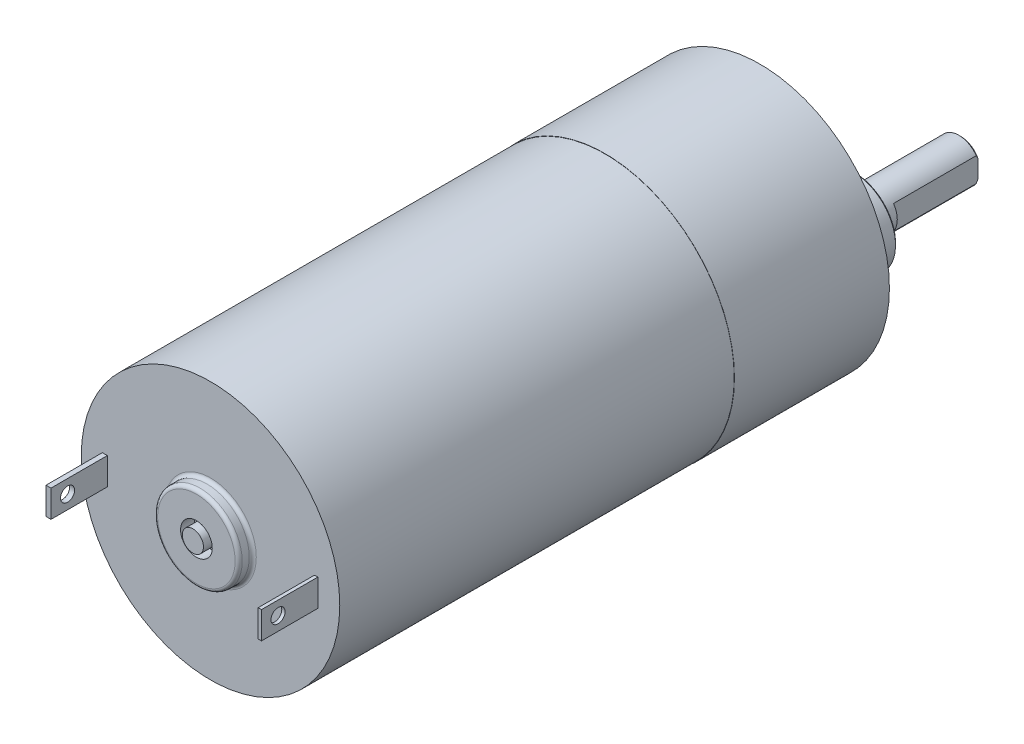
SolidWorks part; units mm, degrees
ref_plane "Plan de face" through (0, 0, 0) normal (0, 0, 1) x (1, 0, 0)
ref_plane "Plan de dessus" through (0, 0, 0) normal (0, 1, 0) x (1, 0, 0)
ref_plane "Plan de droite" through (0, 0, 0) normal (1, 0, 0) x (0, 0, -1)
sketch "Esquisse1" plane through (0, 0, 0) normal (0, 0, 1) x (1, 0, 0)
  circle A0 centre (0, 0) radius 18.385
  dimension "D1" = 36.77
extrude "Boss.-Extru.1" add sketch "Esquisse1" along normal blind 22
sketch "Esquisse2" plane through (0, 0, 22) normal (0, 0, 1) x (1, 0, 0)
  circle A0 centre (0, 0) radius 18.35
  dimension "D1" = 36.7
extrude "Boss.-Extru.2" add sketch "Esquisse2" along normal blind 56
sketch "Esquisse3" plane through (0, 0, 78) normal (0, 0, 1) x (1, 0, 0)
  circle A0 centre (0, 0) radius 6
  dimension "D1" = 12
extrude "Boss.-Extru.3" add sketch "Esquisse3" along normal blind 2
fillet "Congé1" radius 0.5 2 edges at (6, 0, 78) (6, 0, 80)
sketch "Esquisse4" plane through (0, 0, 80) normal (0, 0, 1) x (1, 0, 0)
  circle A0 centre (0, 0) radius 2.25
  dimension "D1" = 4.5
extrude "Enlèv. mat.-Extru.1" cut sketch "Esquisse4" against normal blind 2
sketch "Esquisse5" plane through (0, 0, 78) normal (0, 0, 1) x (1, 0, 0)
  circle A0 centre (0, 0) radius 1.5
  dimension "D1" = 3
extrude "Boss.-Extru.4" add sketch "Esquisse5" along normal blind 2.5
ref_plane "Plan1" through (0, 0, 74.5) normal (0, 0, 1) x (1, 0, 0)
sketch "Esquisse7" plane through (0, 0, 74.5) normal (0, 0, 1) x (1, 0, 0)
  circle A0 centre (0, 0) radius 15.25
  circle A1 centre (0, 0) radius 15.5
  dimension "D1" = 30.5
  dimension "D2" = 31
extrude "Boss.-Extru.5" add sketch "Esquisse7" against normal blind 50 separate body
sketch "Esquisse8" plane through (0, 0, 0) normal (0, 0, -1) x (-1, 0, 0)
  line L0 (-18.385, 0) -> (-18.5, 13.0609) construction
  line L1 (-13.5, 0) -> (-13.5, 12.4803) construction
  circle A0 centre (-7.5, 0) radius 6
  circle A1 centre (0, 0) radius 18.385 construction
  dimension "D1" = 12
  dimension "D2" = 7.5
extrude "Boss.-Extru.6" add sketch "Esquisse8" along normal blind 6 separate body
sketch "Esquisse9" plane through (0, 0, -6) normal (0, 0, -1) x (-1, 0, 0)
  circle A0 centre (-7.5, 0) radius 3
extrude "Boss.-Extru.7" add sketch "Esquisse9" along normal blind 15
sketch "Esquisse10" plane through (0, 0, -21) normal (0, 0, -1) x (-1, 0, 0)
  line L0 (-9.96, 1.7171) -> (-9.96, -1.7171)
  line L1 (-9.96, -1.7171) -> (-14.4902, -1.7171)
  line L2 (-14.4902, -1.7171) -> (-14.4902, 1.7171)
  line L3 (-14.4902, 1.7171) -> (-9.96, 1.7171)
  line L4 (-4.5, 0) -> (-4.5, 4.1694) construction
  circle A0 centre (-7.5, 0) radius 3 construction
  circle A1 centre (-7.5, 0) radius 3 construction
  dimension "D1" = 5.46
extrude "Enlèv. mat.-Extru.5" cut sketch "Esquisse10" against normal blind 12
sketch "Esquisse11" plane through (0, 0, 0) normal (0, 0, -1) x (-1, 0, 0)
  arc A0 (-12.15, -5.8845) -> (-12.15, 5.8845) centre (0, 0) ccw
  arc A1 (-12.15, -5.8845) -> (-12.15, 5.8845) centre (-7.5, 0) ccw
extrude "Enlèv. mat.-Extru.6" cut sketch "Esquisse11" against normal blind 1
fillet "Congé2" radius 0.25 4 edges at (0, 0, 1) (-13.5, 0, 1) (-13.5, 0, 0) (0, 0, 0)
chamfer "Chanfrein1" distance 0.25 angle 45 2 edges at (4.5, 0, -21) (1.5, 0, -6)
sketch "Esquisse12" plane through (0, 0, 0) normal (0, 0, -1) x (-1, 0, 0)
  line L0 (0, 15.5) -> (0, 0) construction
  line L1 (0, 0) -> (0, -15.5) construction
  circle A0 centre (0, 15.5) radius 0.9142
  circle A1 centre (0, -15.5) radius 0.7448
  circle A2 centre (13.4234, 7.75) radius 0.9142
  circle A3 centre (13.4234, -7.75) radius 0.9142
  circle A4 centre (0, -15.5) radius 0.9142
  circle A5 centre (-13.4234, -7.75) radius 0.9142
  circle A6 centre (-13.4234, 7.75) radius 0.9142
  point P19 (0, 0)
  dimension "D1" = 31
  dimension "D2" = 6
hole_wizard "Trou taraudé M31" positions "Esquisse3D1" profile "Esquisse13" tap size "M3" standard "ISO"
sketch3d "Esquisse3D1"
  point P0 (0, 15.5, 0)
  point P3 (13.4234, 7.75, 0)
  point P6 (13.4234, -7.75, 0)
  point P9 (0, -15.5, 0)
  point P12 (-13.4234, -7.75, 0)
  point P15 (-13.4234, 7.75, 0)
sketch "Esquisse13" plane through (0, 15.5, 0) normal (1, 0, 0) x (0, 1, 0)
  line L0 (0, 0) -> (0, 5.7511)
  line L1 (0, 5.7511) -> (1.25, 5)
  line L2 (1.25, 5) -> (1.25, 0)
  line L5 (1.25, 0) -> (0, 0)
  line L10 (0, 5.7511) -> (-1.25, 5) construction
  line L11 (0, -6.35) -> (0, 107.95) construction
  dimension "Diamètre du trou pour taraudage" = 2.5
  dimension "Profondeur du trou pour taraudage" = 5
  dimension "Angle de pointe" = 118
cosmetic thread "Filetage de perçage1" parameters "D1"=5, "D2"=3
cosmetic thread "Filetage de perçage2" parameters "D1"=5, "D2"=3
cosmetic thread "Filetage de perçage3" parameters "D1"=5, "D2"=3
cosmetic thread "Filetage de perçage4" parameters "D1"=5, "D2"=3
cosmetic thread "Filetage de perçage5" parameters "D1"=5, "D2"=3
cosmetic thread "Filetage de perçage6" parameters "D1"=5, "D2"=3
sketch "Esquisse14" plane through (0, 0, 78) normal (0, 0, 1) x (1, 0, 0)
  line L0 (0, 0) -> (24.8231, 0) construction
  line L1 (14.7638, 1.925) -> (15.2362, 1.925)
  line L2 (14.7638, 1.925) -> (14.7638, -1.925)
  line L3 (14.7638, -1.925) -> (15.2362, -1.925)
  line L4 (15.2362, 1.925) -> (15.2362, -1.925)
  line L5 (14.7638, 1.925) -> (15.2362, -1.925) construction
  line L6 (14.7638, -1.925) -> (15.2362, 1.925) construction
  line L7 (-15.3543, 1.925) -> (-14.6457, 1.925)
  line L8 (-15.3543, 1.925) -> (-15.3543, -1.925)
  line L9 (-15.3543, -1.925) -> (-14.6457, -1.925)
  line L10 (-14.6457, 1.925) -> (-14.6457, -1.925)
  line L11 (-15.3543, 1.925) -> (-14.6457, -1.925) construction
  line L12 (-15.3543, -1.925) -> (-14.6457, 1.925) construction
  line L13 (0, 0) -> (-30.602, 0) construction
  point P0 (15, 0)
  point P5 (-15, 0)
  dimension "D1" = 3.85
  dimension "D2" = 3.85
  dimension "D3" = 15
  dimension "D4" = 15
extrude "Boss.-Extru.8" add sketch "Esquisse14" along normal blind 8
sketch "Esquisse15" plane through (-15.3543, 0, 0) normal (-1, 0, 0) x (0, 0, 1)
  circle A0 centre (83.6484, 0) radius 1
  dimension "D1" = 2
extrude "Enlèv. mat.-Extru.7" cut sketch "Esquisse15" against normal blind 38
